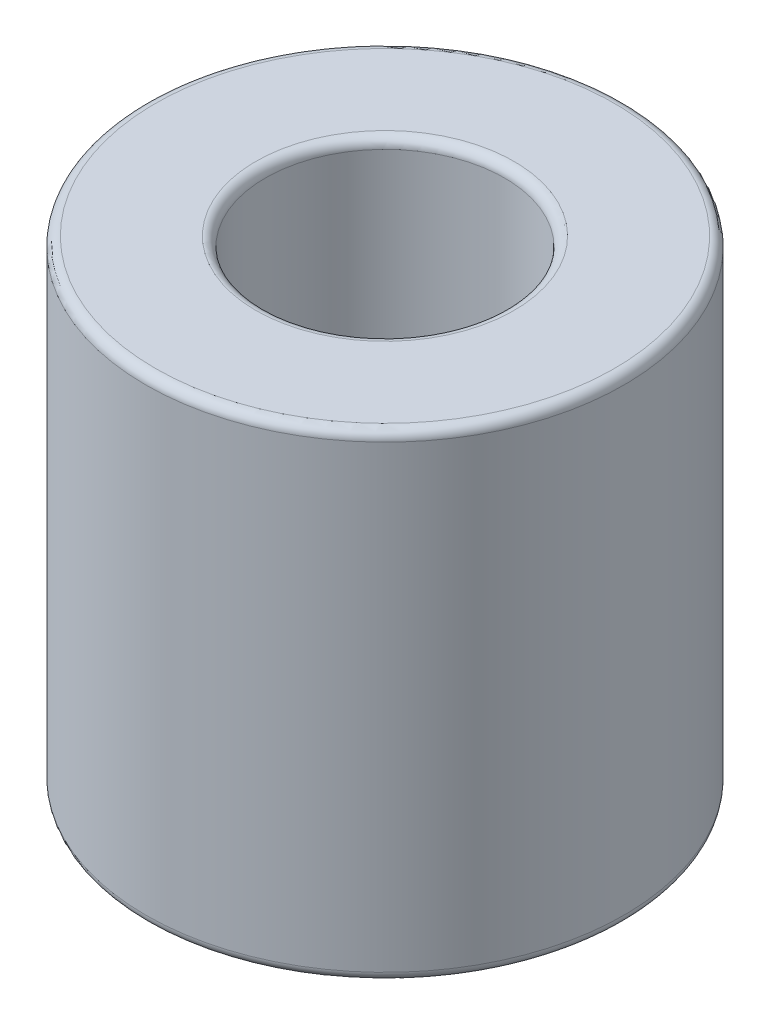
SolidWorks part; units mm, degrees
material "Leaded Commercial Bronze"
ref_plane "Front" through (0, 0, 0) normal (0, 0, 1) x (1, 0, 0)
ref_plane "Top" through (0, 0, 0) normal (0, 1, 0) x (1, 0, 0)
ref_plane "Right" through (0, 0, 0) normal (1, 0, 0) x (0, 0, -1)
sketch "Sketch1" plane through (0, 0, 0) normal (0, 1, 0) x (1, 0, 0)
  circle A0 centre (0, 0) radius 3.175
  dimension "D1" = 6.35
extrude "Boss-Extrude1" add sketch "Sketch1" along normal blind 6.35 contours A0
sketch "Sketch2" plane through (0, 6.35, 0) normal (0, 1, 0) x (1, 0, 0)
  circle A0 centre (0, 0) radius 1.5875
  dimension "D1" = 3.175
extrude "Cut-Extrude1" cut sketch "Sketch2" against normal through all
fillet "Fillet1" radius 0.127 4 edges at (0, 0, 1.5875) (0, 0, 3.175) (0, 6.35, 1.5875) (0, 6.35, 3.175)
